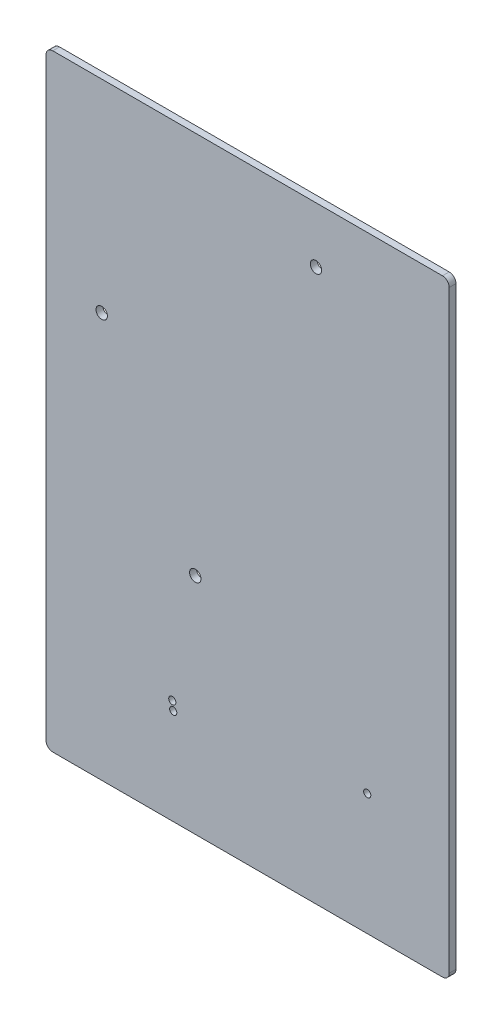
SolidWorks part; units mm, degrees
material "PC High Viscosity"
ref_plane "Front Plane" through (0, 0, 0) normal (0, 0, 1) x (1, 0, 0)
ref_plane "Top Plane" through (0, 0, 0) normal (0, 1, 0) x (1, 0, 0)
ref_plane "Right Plane" through (0, 0, 0) normal (1, 0, 0) x (0, 0, -1)
sketch "Sketch1" plane through (0, 0, 0) normal (0, 0, 1) x (1, 0, 0)
  line L0 (0, 0) -> (0, 571.5)
  line L1 (0, 0) -> (379.4125, 0)
  line L2 (381, 355.6) -> (425.45, 355.6) construction
  line L3 (381, 355.6) -> (381, 400.05) construction
  line L4 (381, 400.05) -> (425.45, 400.05) construction
  line L5 (425.45, 355.6) -> (425.45, 400.05) construction
  line L6 (379.4125, 0) -> (379.4125, 403.225)
  line L7 (379.4125, 403.225) -> (428.625, 403.225)
  line L8 (428.625, 403.225) -> (428.625, 355.6)
  line L9 (428.625, 355.6) -> (479.425, 355.6)
  line L10 (479.425, 355.6) -> (479.425, 466.725)
  line L12 (379.4125, 571.5) -> (0, 571.5)
  line L13 (379.4125, 571.5) -> (379.4125, 466.725)
  line L14 (379.4125, 466.725) -> (479.425, 466.725)
  dimension "D1" = 571.5
  dimension "D2" = 44.45
  dimension "D3" = 400.05
  dimension "D4" = 381
  dimension "D5" = 3.175
  dimension "D6" = 3.175
  dimension "D7" = 3.175
  dimension "D8" = 50.8
  dimension "D9" = 63.5
extrude "Boss-Extrude1" add sketch "Sketch1" along normal blind 6.35
fillet "Fillet1" radius 3.175 2 edges at (428.625, 403.225, 3.175) (379.4125, 403.225, 3.175)
fillet "Fillet2" radius 44.45 2 edges at (479.425, 466.725, 3.175) (379.4125, 466.725, 3.175)
hole_wizard "1/4 Clearance Hole1" positions "Sketch2" profile "Sketch3" hole size "1/4" standard "ANSI Inch" end condition through all
sketch "Sketch2" plane through (0, 0, 0) normal (0, 0, -1) x (-1, 0, 0)
  line L0 (0, 77.4886) -> (-379.4125, 110.6829) construction
  line L1 (0, 571.5) -> (0, 0) construction
  line L2 (-379.4125, 0) -> (-379.4125, 400.05) construction
  line L4 (0, 0) -> (-379.4125, 0) construction
  line L5 (-320.0116, 93.5432) -> (-104.9332, 74.7262) construction
  line L6 (-320.0116, 93.5432) -> (-316.691, 131.4982) construction
  line L7 (-104.9332, 74.7262) -> (-101.6126, 112.6813) construction
  line L8 (-316.691, 131.4982) -> (-101.6126, 112.6813) construction
  line L9 (-319.8049, 95.9065) -> (-104.7264, 77.0896) construction
  line L11 (0, 0) -> (-44.45, 0) construction
  line L12 (0, 0) -> (0, 571.5) construction
  line L13 (0, 571.5) -> (-44.45, 571.5) construction
  line L14 (-44.45, 0) -> (-44.45, 571.5) construction
  line L15 (-379.4125, 571.5) -> (0, 571.5) construction
  line L17 (-381, 0) -> (-425.45, 0) construction
  line L18 (-381, 0) -> (-381, 571.5) construction
  line L19 (-381, 571.5) -> (-425.45, 571.5) construction
  line L20 (-425.45, 0) -> (-425.45, 571.5) construction
  line L21 (-379.4125, 121.05) -> (-44.45, 91.7445) construction
  line L23 (-209.1518, 122.0897) -> (-212.4724, 84.1347) construction
  line L24 (-318.9747, 105.3953) -> (-103.8963, 86.5783) construction
  line L25 (-319.6665, 97.488) -> (-104.5881, 78.671) construction
  line L27 (-104.4497, 80.2525) -> (-319.5281, 99.0694) construction
  line L28 (-425.45, 44.45) -> (0, 44.45) construction
  line L29 (-302.26, 114.3) -> (-119.6854, 90.2636) construction
  point P0 (-118.8107, 98.2503)
  point P2 (-302.26, 114.3)
  point P213 (-209.1518, 122.0897)
  point P230 (-119.6854, 90.2636)
  point P235 (-131.0873, 91.7647)
  dimension "D3" = 2.3724
  dimension "D4" = 38.1
  dimension "D5" = 215.9
  dimension "D6" = 44.45
  dimension "D7" = 0
  dimension "D8" = 381
  dimension "D9" = 15.875
  dimension "D10" = 184.15
  dimension "D11" = 1.5875
  dimension "D12" = 1.5875
  dimension "D13" = 6.35
  dimension "D14" = 44.45
  dimension "D2" = 5
  dimension "D16" = 114.3
  dimension "D15" = 302.26
  dimension "D17" = 7.5
  dimension "D18" = 184.15
sketch "Sketch3" plane through (118.8107, 98.2503, 0) normal (1, 0, 0) x (0, 1, 0)
  line L0 (0, 0) -> (0, 6.35)
  line L1 (0, 6.35) -> (3.3782, 6.35)
  line L2 (3.3782, 6.35) -> (3.3782, 0)
  line L5 (3.3782, 0) -> (0, 0)
  line L11 (0, -6.35) -> (0, 107.95) construction
  dimension "Thru Hole Dia." = 6.7564
  dimension "Thru Hole Depth" = 6.35
sketch "Sketch4" plane through (0, 0, 0) normal (0, 0, -1) x (-1, 0, 0)
  line L1 (-379.4125, 511.175) -> (-479.425, 511.175)
  line L2 (-379.4125, 511.175) -> (-379.4125, 355.6)
  line L3 (-379.4125, 355.6) -> (-479.425, 355.6)
  line L4 (-479.425, 511.175) -> (-479.425, 355.6)
extrude "Cut-Extrude1" cut sketch "Sketch4" against normal through all
hole_wizard "27/64 (0.42188) Diameter Hole1" positions "Sketch6" profile "Sketch7" hole size "27/64" standard "ANSI Inch" end condition through all
sketch "Sketch6" plane through (0, 0, 0) normal (0, 0, -1) x (-1, 0, 0)
  line L0 (-44.45, 571.5) -> (-44.45, 0) construction
  line L1 (0, 571.5) -> (0, 0) construction
  line L2 (0, 0) -> (-379.4125, 0) construction
  line L3 (0, 381) -> (-52.3875, 381) construction
  line L4 (-254, 571.5) -> (-254, 519.1125) construction
  line L5 (-379.4125, 571.5) -> (0, 571.5) construction
  line L6 (-379.4125, 571.5) -> (0, 571.5) construction
  line L7 (0, 0) -> (-379.4125, 0) construction
  point P0 (-254, 519.1125)
  point P2 (-52.3875, 381)
  point P4 (-140.462, 210.82)
  dimension "D1" = 44.45
  dimension "D2" = 7.9375
  dimension "D3" = 210.82
  dimension "D4" = 381
  dimension "D5" = 254
  dimension "D6" = 140.462
sketch "Sketch7" plane through (254, 519.1125, 0) normal (1, 0, 0) x (0, 1, 0)
  line L0 (0, 0) -> (0, 6.35)
  line L1 (0, 6.35) -> (5.3579, 6.35)
  line L2 (5.3579, 6.35) -> (5.3579, 0)
  line L5 (5.3579, 0) -> (0, 0)
  line L11 (0, -6.35) -> (0, 107.95) construction
  dimension "Thru Hole Dia." = 10.7158
  dimension "Thru Hole Depth" = 6.35
fillet "Fillet3" radius 6.35 4 edges at (379.4125, 0, 3.175) (0, 571.5, 3.175) (379.4125, 571.5, 3.175) (0, 0, 3.175)
equation "\"D18@Sketch2\"=\"D10@Sketch2\""
